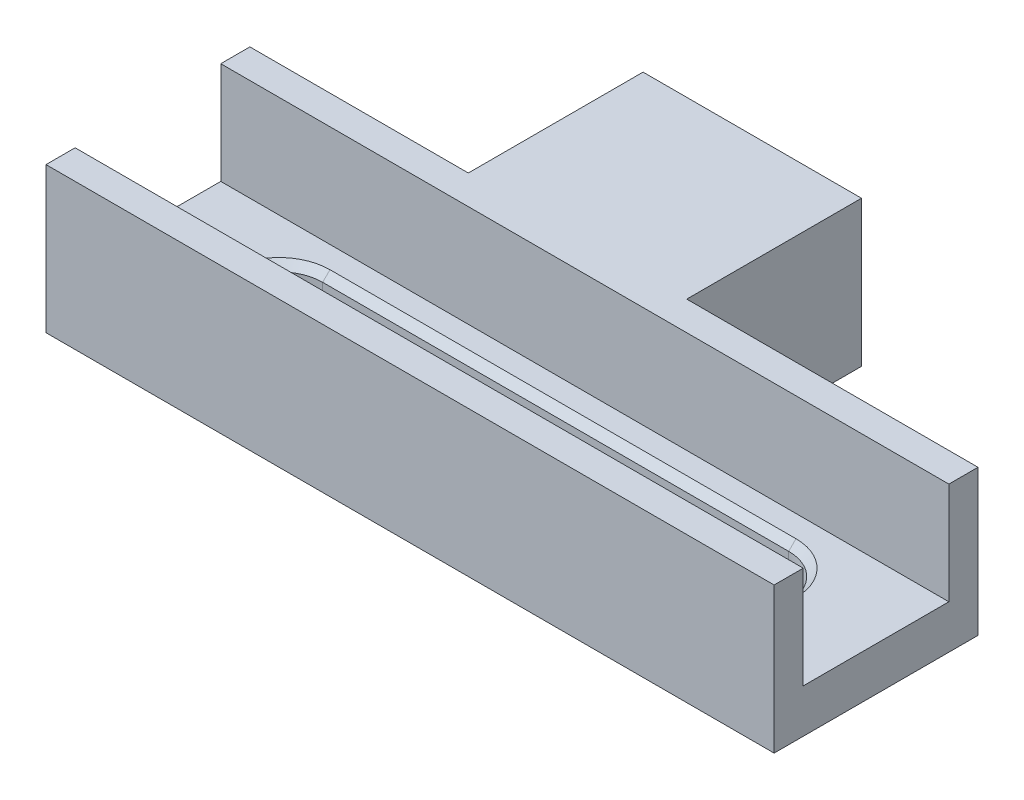
SolidWorks part; units mm, degrees
ref_plane "Front Plane" through (0, 0, 0) normal (0, 0, 1) x (1, 0, 0)
ref_plane "Top Plane" through (0, 0, 0) normal (0, 1, 0) x (1, 0, 0)
ref_plane "Right Plane" through (0, 0, 0) normal (1, 0, 0) x (0, 0, -1)
sketch "Sketch1" plane through (0, 0, 0) normal (0, 1, 0) x (1, 0, 0)
  line L0 (-10, 7) -> (-10, 19)
  line L1 (-25, 7) -> (-10, 7)
  line L2 (-25, 7) -> (-25, -7)
  line L3 (-25, -7) -> (25, -7)
  line L4 (25, 7) -> (25, -7)
  line L5 (-25, 7) -> (25, -7) construction
  line L6 (-25, -7) -> (25, 7) construction
  line L7 (-10, 19) -> (5, 19)
  line L8 (5, 19) -> (5, 7)
  line L9 (5, 7) -> (25, 7)
  point P0 (0, 0)
  dimension "D1" = 50
  dimension "D2" = 14
  dimension "D3" = 26
  dimension "D4" = 15
  dimension "D5" = 15
extrude "Boss-Extrude1" add sketch "Sketch1" along normal blind 10
sketch "Sketch2" plane through (-25, 0, 0) normal (-1, 0, 0) x (0, 0, 1)
  line L0 (5, 3) -> (-5, 3)
  line L2 (-5, 3) -> (-5, 10)
  line L3 (-7, 10) -> (7, 10) construction
  line L4 (0, 0) -> (0, 13.4605) construction
  line L5 (5, 3) -> (5, 10)
  line L6 (-5, 10) -> (5, 10)
  dimension "D1" = 5
  dimension "D2" = 7
extrude "Cut-Extrude2" cut sketch "Sketch2" against normal blind 71
sketch "Sketch4" plane through (0, 0, 0) normal (0, 1, 0) x (1, 0, 0)
  line L0 (-16, 0) -> (16, 0) construction
  line L1 (-16, 0) -> (16, 0) construction
  line L2 (-16, 3) -> (16, 3)
  line L3 (-16, -3) -> (16, -3)
  arc A0 (-16, 3) -> (-16, -3) centre (-16, 0) ccw
  arc A1 (16, -3) -> (16, 3) centre (16, 0) ccw
  point P0 (0, 0)
  point P4 (0, 0)
  dimension "D1" = 32
  dimension "D2" = 6
extrude "Cut-Extrude3" cut sketch "Sketch4" along normal blind 71
sketch "Sketch5" plane through (0, 0, -19) normal (0, 0, -1) x (-1, 0, 0)
  line L4 (0, 0) -> (0, 10) construction
  line L5 (-5, 10) -> (10, 10) construction
  circle A0 centre (0, 5) radius 2.5
  dimension "D1" = 5
hole_wizard "#5 (0.19685) Diameter Hole1" positions "Sketch6" profile "Sketch7" hole size "#5" standard "ANSI Inch"
sketch "Sketch6" plane through (0, 0, -19) normal (0, 0, -1) x (-1, 0, 0)
  point P0 (0, 5)
sketch "Sketch7" plane through (0, 5, -19) normal (1, 0, 0) x (0, 1, 0)
  line L0 (0, 0) -> (0, 11.5021)
  line L1 (0, 11.5021) -> (2.5, 10)
  line L2 (2.5, 10) -> (2.5, 0)
  line L5 (2.5, 0) -> (0, 0)
  line L10 (0, 11.5021) -> (-2.5, 10) construction
  line L11 (0, -6.35) -> (0, 107.95) construction
  dimension "Hole Dia." = 5
  dimension "Hole Depth" = 10
  dimension "Drill Angle" = 118
sketch "Sketch8" plane through (-10, 0, 0) normal (-1, 0, 0) x (0, 0, 1)
  line L0 (-19, 5) -> (-7, 5) construction
  line L1 (-19, 0) -> (-19, 10) construction
  line L2 (-7, 10) -> (-7, 0) construction
  circle A0 centre (-13, 5) radius 2.25
  dimension "D1" = 4.5
extrude "Cut-Extrude4" cut sketch "Sketch8" against normal up to surface (7.5 mm away) up to face at (-2.5, 5, -9)
chamfer "Chamfer1" distance 0.5 angle 45 10 edges at (0, 0, -3) (-19, 0, 0) (19, 0, 0) (0, 0, 3) (0, 3, -3) (-19, 3, 0) (19, 3, 0) (0, 3, 3) (-10, 5, -10.75) (-2.5, 5, -19)
